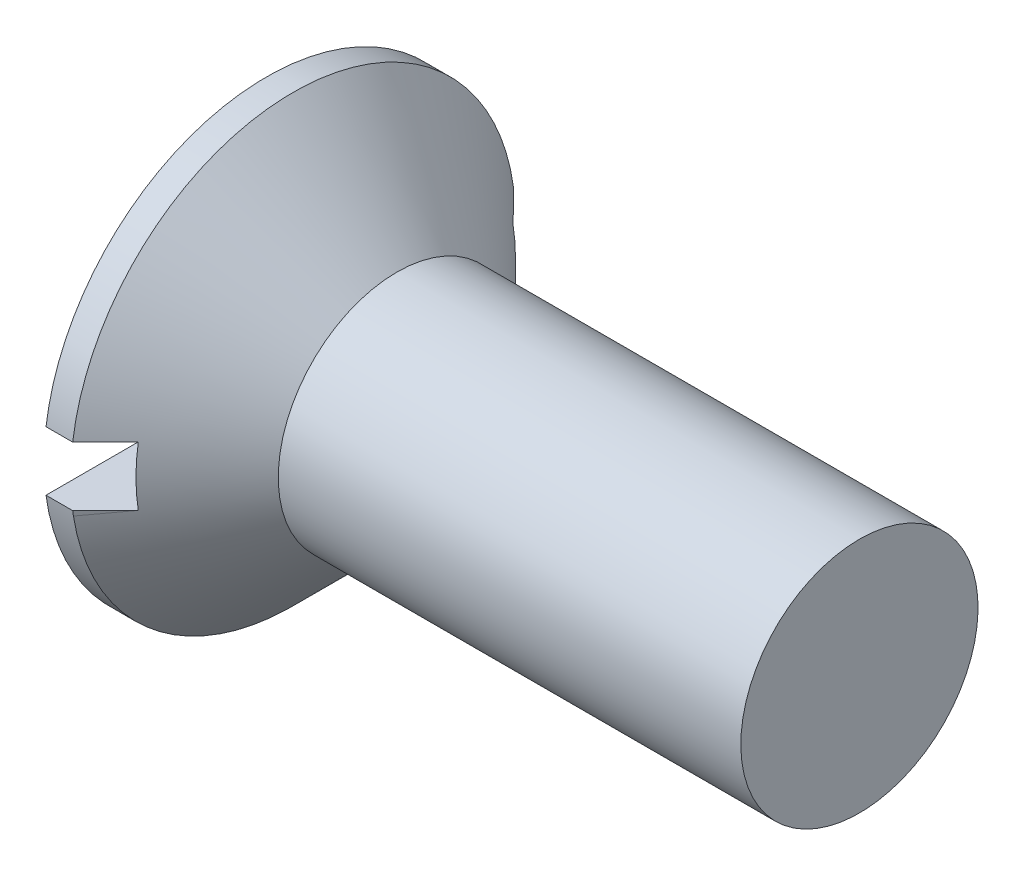
SolidWorks part; units mm, degrees
material "Plain Carbon Steel"
ref_plane "Front Plane" through (0, 0, 0) normal (0, 0, 1) x (1, 0, 0)
ref_plane "Top Plane" through (0, 0, 0) normal (0, 1, 0) x (1, 0, 0)
ref_plane "Right Plane" through (0, 0, 0) normal (1, 0, 0) x (0, 0, -1)
sketch "Sketch1" plane through (0, 0, 0) normal (0, 0, 1) x (1, 0, 0)
  line L0 (0, 0) -> (0, 3.75)
  line L1 (0, 3.75) -> (0.45, 3.75)
  line L2 (0.45, 3.75) -> (2.2, 2)
  line L3 (2.2, 2) -> (10, 2)
  line L4 (10, 2) -> (10, 0)
  line L5 (10, 0) -> (0, 0) construction
  line L6 (0, 0) -> (10, 0)
  dimension "D1" = 45
  dimension "D2" = 4
  dimension "D3" = 7.5
  dimension "D4" = 2.2
  dimension "D5" = 10
revolve "Revolve1" add sketch "Sketch1" angle 360 about L5
sketch "Sketch2" plane through (0, 0, 0) normal (-1, 0, 0) x (0, 0, 1)
  line L0 (3.75, 0) -> (-3.75, 0) construction
  line L1 (-3.75, 0.5) -> (3.75, 0.5)
  line L2 (-3.75, 0.5) -> (-3.75, -0.5)
  line L3 (-3.75, -0.5) -> (3.75, -0.5)
  line L4 (3.75, 0.5) -> (3.75, -0.5)
  circle A0 centre (0, 0) radius 3.75 construction
  dimension "D1" = 1
extrude "Cut-Extrude1" cut sketch "Sketch2" against normal blind 1
